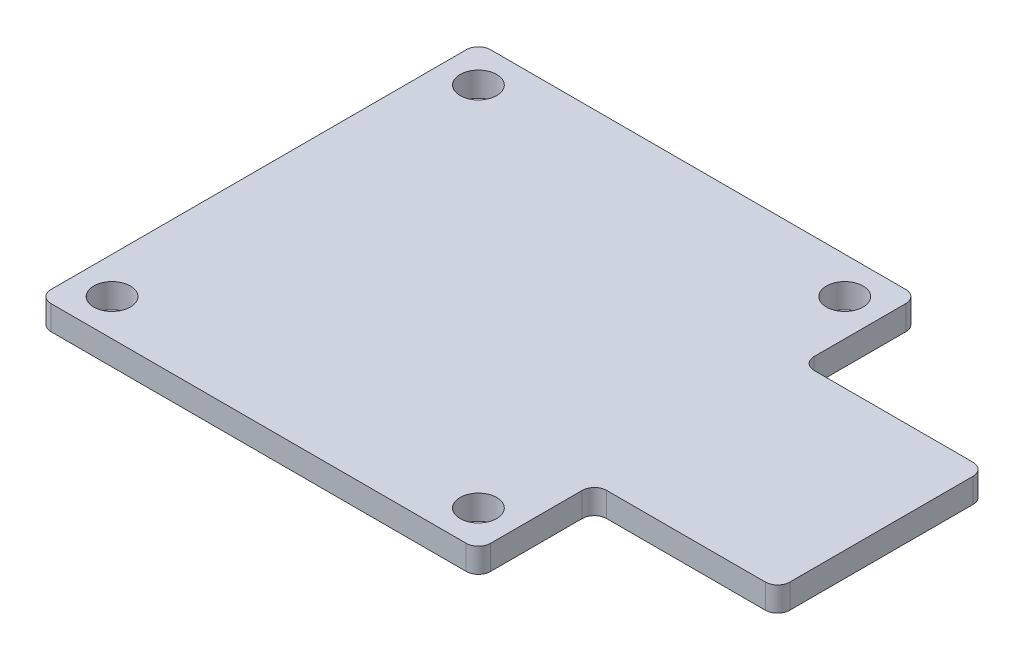
SolidWorks part; units mm, degrees
ref_plane "Front" through (0, 0, 0) normal (0, 0, 1) x (1, 0, 0)
ref_plane "Top" through (0, 0, 0) normal (0, 1, 0) x (1, 0, 0)
ref_plane "Right" through (0, 0, 0) normal (1, 0, 0) x (0, 0, -1)
sketch "Sketch1" plane through (0, 0, 0) normal (0, 1, 0) x (1, 0, 0)
  line L1 (0, 0) -> (36, 0)
  line L2 (0, 0) -> (0, 36)
  line L3 (0, 36) -> (36, 36)
  line L4 (36, 0) -> (36, 36)
  line L5 (36, 9.5) -> (51, 9.5)
  line L6 (36, 9.5) -> (36, 26.5)
  line L7 (36, 26.5) -> (51, 26.5)
  line L8 (51, 9.5) -> (51, 26.5)
  circle A0 centre (3, 33) radius 1.5
  circle A1 centre (33, 33) radius 1.5
  circle A2 centre (3, 3) radius 1.5
  circle A3 centre (33, 3) radius 1.5
  point P9 (51, 18)
  dimension "D6" = 3
  dimension "D9" = 3
  dimension "D10" = 3
  dimension "D13" = 3
  dimension "D14" = 3
  dimension "D1" = 36
  dimension "D2" = 36
  dimension "D3" = 15
  dimension "D4" = 17
  dimension "D5" = 18
  dimension "D7" = 3
  dimension "D8" = 3
  dimension "D11" = 3
  dimension "D12" = 3
extrude "Boss-Extrude1" add sketch "Sketch1" along normal blind 2 contours L1 L4 L3 L2 A3 A2 A1 A0 | L5 L8 L7 L4
fillet "Fillet1" radius 1 8 edges at (51, 1, -9.5) (51, 1, -26.5) (36, 1, -26.5) (36, 1, -9.5) (0, 1, 0) (36, 1, 0) (36, 1, -36) (0, 1, -36)
